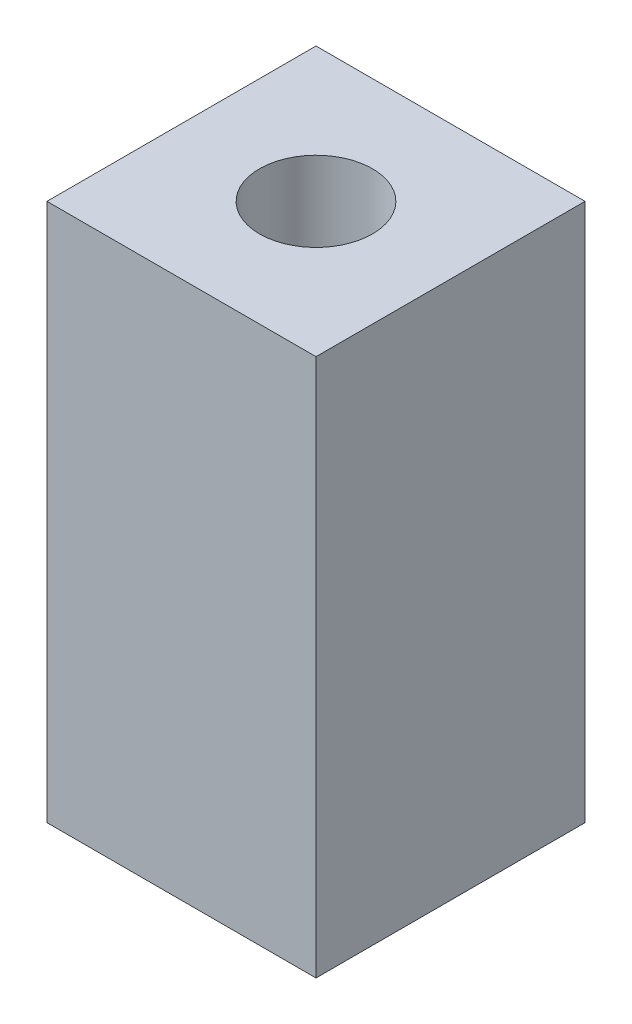
SolidWorks part; units mm, degrees
ref_plane "Front" through (0, 0, 0) normal (0, 0, 1) x (1, 0, 0)
ref_plane "Top" through (0, 0, 0) normal (0, 1, 0) x (1, 0, 0)
ref_plane "Right" through (0, 0, 0) normal (1, 0, 0) x (0, 0, -1)
sketch "Sketch1" plane through (0, 0, 0) normal (0, 1, 0) x (1, 0, 0)
  line L1 (2.5, -2.5) -> (-2.5, -2.5)
  line L2 (2.5, -2.5) -> (2.5, 2.5)
  line L3 (2.5, 2.5) -> (-2.5, 2.5)
  line L4 (-2.5, -2.5) -> (-2.5, 2.5)
  line L5 (2.5, -2.5) -> (-2.5, 2.5) construction
  line L6 (2.5, 2.5) -> (-2.5, -2.5) construction
  point P0 (0, 0)
  dimension "D1" = 5
  dimension "D2" = 5
extrude "Boss-Extrude1" add sketch "Sketch1" along normal mid plane 10
sketch "Sketch2" plane through (0, 5, 0) normal (0, 1, 0) x (1, 0, 0)
  circle A0 centre (0, 0) radius 1.05
  dimension "D1" = 2.1
extrude "Cut-Extrude1" cut sketch "Sketch2" against normal blind 3
sketch "Sketch3" plane through (0, -5, 0) normal (0, -1, 0) x (1, 0, 0)
  circle A0 centre (0, 0) radius 1.05
  dimension "D1" = 2.1
extrude "Cut-Extrude2" cut sketch "Sketch3" against normal blind 3
